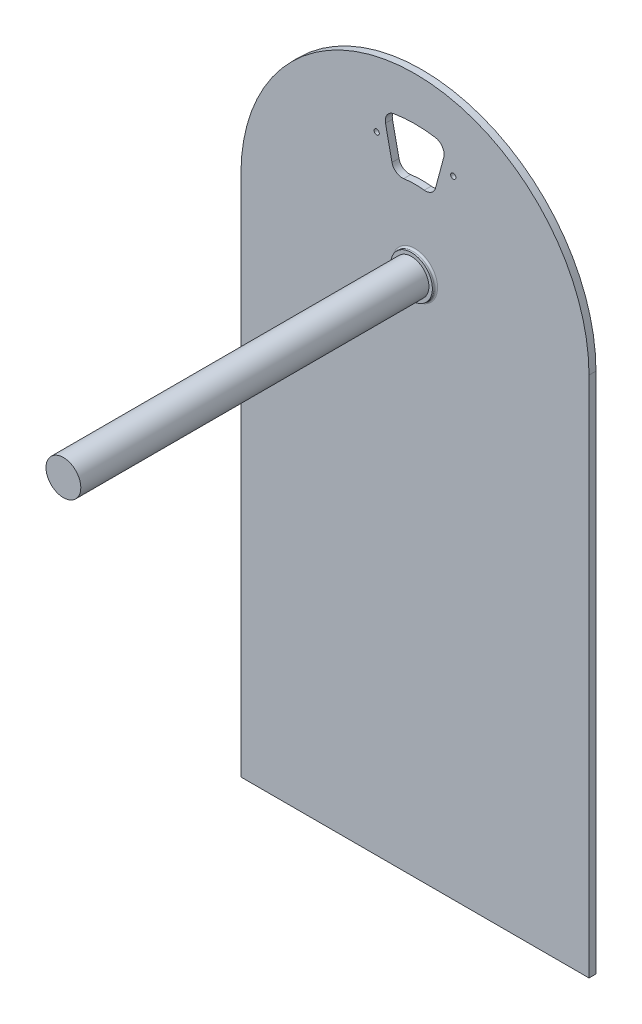
SolidWorks part; units mm, degrees
material "ABS"
ref_plane "前视基准面" through (0, 0, 0) normal (0, 0, 1) x (1, 0, 0)
ref_plane "上视基准面" through (0, 0, 0) normal (0, 1, 0) x (1, 0, 0)
ref_plane "右视基准面" through (0, 0, 0) normal (1, 0, 0) x (0, 0, -1)
other "Configuration Table"
sketch "草图1" plane through (0, 0, 0) normal (0, 0, 1) x (1, 0, 0)
  line L0 (0, -1000) -> (0, 49000) construction
  line L1 (-8.4649, 33.4301) -> (-6.5907, 24.6128)
  line L2 (8.2674, 33.3031) -> (5.9204, 24.5438)
  circle A0 centre (0, 0) radius 50
  arc A1 (5.8366, 37.043) -> (-6.0114, 37.015) centre (0, 0) ccw
  arc A2 (2.667, 22.3414) -> (-3.2261, 22.2675) centre (0, 0) ccw
  arc A3 (5.9204, 24.5438) -> (2.667, 22.3414) centre (3.0226, 25.3202) cw
  arc A4 (8.2674, 33.3031) -> (5.8366, 37.043) centre (5.3696, 34.0796) ccw
  arc A5 (-8.4649, 33.4301) -> (-6.0114, 37.015) centre (-5.5305, 34.0538) cw
  arc A6 (-6.5907, 24.6128) -> (-3.2261, 22.2675) centre (-3.6563, 25.2365) ccw
  point P13 (9.0921, 36.3811)
  point P16 (-9.0921, 36.3811)
  dimension "D1" = 100
  dimension "D2" = 75
  dimension "D3" = 45
  dimension "D5" = 3
  dimension "D4" = 12
extrude "凸台-拉伸1" add sketch "草图1" along normal blind 2
sketch "草图2" plane through (0, 0, 2) normal (0, 0, 1) x (1, 0, 0)
  circle A0 centre (0, 0) radius 6
  dimension "D1" = 12
extrude "凸台-拉伸2" add sketch "草图2" along normal blind 1
sketch "草图3" plane through (0, 0, 3) normal (0, 0, 1) x (1, 0, 0)
  circle A0 centre (0, 0) radius 5
  dimension "D1" = 10
extrude "凸台-拉伸3" add sketch "草图3" along normal blind 100
fillet "圆角1" radius 0.5 1 edges at (6, 0, 2)
sketch "草图4" plane through (0, 0, 0) normal (0, 0, -1) x (-1, 0, 0)
  line L0 (-1002.621, 30) -> (48997.379, 30) construction
  line L1 (0, -1000) -> (0, 49000) construction
  circle A0 centre (-11, 30) radius 0.75
  circle A1 centre (11, 30) radius 0.75
  dimension "D2" = 1.5
  dimension "D1" = 30
  dimension "D3" = 11
extrude "切除-拉伸1" cut sketch "草图4" against normal blind 10
sketch "草图5" plane through (0, 0, 2) normal (0, 0, 1) x (1, 0, 0)
  line L0 (0, -1000) -> (0, 49000) construction
  line L2 (-50, -150) -> (50, -150)
  line L3 (-50, -150) -> (-50, 0)
  line L4 (-50, 0) -> (50, 0)
  line L5 (50, -150) -> (50, 0)
  line L6 (-50, -150) -> (50, 0) construction
  line L7 (-50, 0) -> (50, -150) construction
  circle A0 centre (0, 0) radius 50 construction
  point P1 (0, -75)
  point P8 (0, -85.2339)
  point P9 (50, 0)
  dimension "D1" = 150
  dimension "D2" = 100
extrude "凸台-拉伸4" add sketch "草图5" against normal up to surface (2 mm away) up to face at (10.25, 30, 0)
